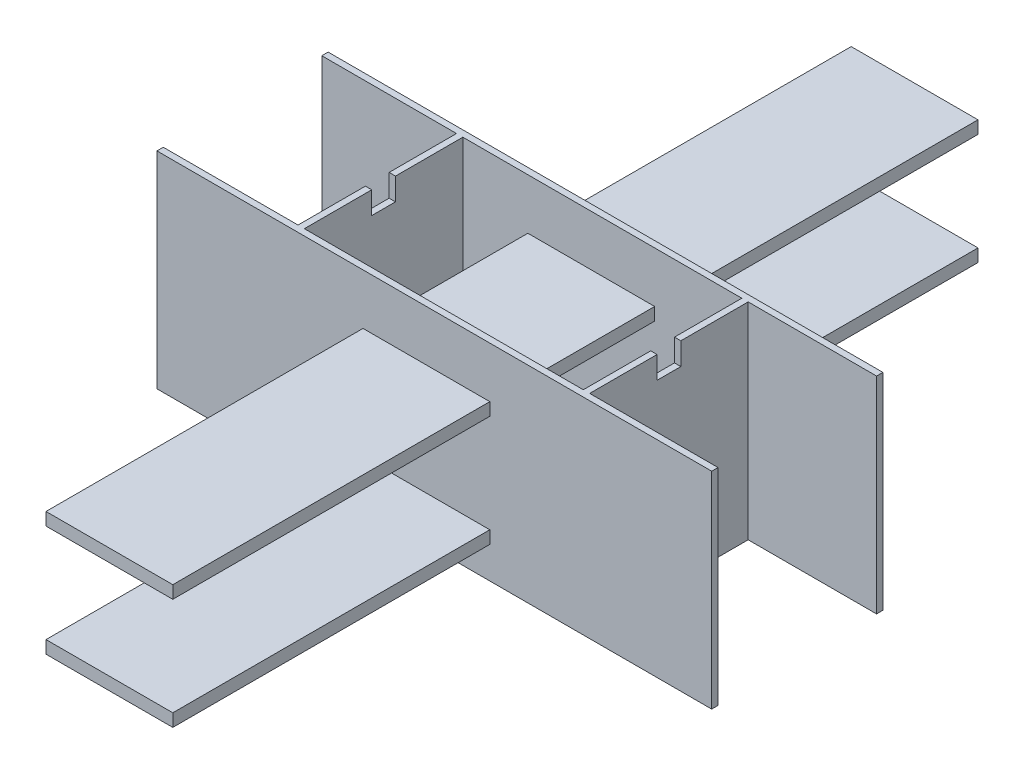
SolidWorks part; units mm, degrees
ref_plane "Front Plane" through (0, 0, 0) normal (0, 0, 1) x (1, 0, 0)
ref_plane "Top Plane" through (0, 0, 0) normal (0, 1, 0) x (1, 0, 0)
ref_plane "Right Plane" through (0, 0, 0) normal (1, 0, 0) x (0, 0, -1)
ref_plane "Plane1" through (0, 0, 25) normal (0, 0, 1) x (1, 0, 0)
sketch "Sketch1" plane through (0, 0, 25) normal (0, 0, 1) x (1, 0, 0)
  line L0 (0, 0) -> (21.8924, 0) construction
  line L1 (-87.5, 32.5) -> (87.5, 32.5)
  line L2 (-87.5, 32.5) -> (-87.5, -32.5)
  line L3 (-87.5, -32.5) -> (87.5, -32.5)
  line L4 (87.5, 32.5) -> (87.5, -32.5)
  line L5 (0, 0) -> (0, 16.4757) construction
  point P5 (0, 0)
  point P9 (0, 0)
  point P10 (-59.809, -32.5)
  dimension "D1" = 65
  dimension "D2" = 175
extrude "Boss-Extrude1" add sketch "Sketch1" along normal blind 2 contours L2 L3 L4 L1
ref_plane "Plane2" through (0, 0, -25) normal (0, 0, 1) x (1, 0, 0)
sketch "Sketch2" plane through (0, 0, -25) normal (0, 0, 1) x (1, 0, 0)
  line L0 (-87.5, -32.5) -> (87.5, -32.5) construction
  line L1 (-87.5, 32.5) -> (-87.5, -32.5) construction
  line L2 (-87.5, 32.5) -> (87.5, 32.5) construction
  line L3 (87.5, 32.5) -> (87.5, -32.5) construction
  line L4 (-87.5, -32.5) -> (87.5, -32.5)
  line L5 (-87.5, 32.5) -> (-87.5, -32.5)
  line L6 (-87.5, 32.5) -> (87.5, 32.5)
  line L7 (87.5, 32.5) -> (87.5, -32.5)
extrude "Boss-Extrude2" add sketch "Sketch2" against normal blind 2 separate body
sketch "Sketch3" plane through (0, 0, 0) normal (0, 0, 1) x (1, 0, 0)
  line L0 (87.5, 0) -> (17.5, 0) construction
  line L1 (87.5, -32.5) -> (87.5, 32.5) construction
  line L2 (17.5, 0) -> (17.5, 16.5) construction
  line L3 (17.5, 0) -> (17.5, -22.5) construction
  line L4 (87.5, 32.5) -> (-87.5, 32.5) construction
  line L5 (-87.5, -32.5) -> (87.5, -32.5) construction
  line L7 (17.5, 16.5) -> (-22.5, 16.5)
  line L8 (17.5, 16.5) -> (17.5, 12.5)
  line L9 (17.5, 12.5) -> (-22.5, 12.5)
  line L10 (-22.5, 16.5) -> (-22.5, 12.5)
  line L11 (17.5, -22.5) -> (-22.5, -22.5)
  line L12 (17.5, -22.5) -> (17.5, -18.5)
  line L13 (17.5, -18.5) -> (-22.5, -18.5)
  line L14 (-22.5, -22.5) -> (-22.5, -18.5)
  dimension "D1" = 70
  dimension "D2" = 16
  dimension "D3" = 10
  dimension "D4" = 4
  dimension "D5" = 4
  dimension "D6" = 40
  dimension "D7" = 40
extrude "Boss-Extrude3" add sketch "Sketch3" along normal blind 127 and the other way blind 127 contours L11 L14 L13 L12 | L7 L10 L9 L8
ref_plane "Plane3" through (45, 0, 0) normal (1, 0, 0) x (0, 0, -1)
ref_plane "Plane4" through (-45, 0, 0) normal (1, 0, 0) x (0, 0, -1)
sketch "Sketch4" plane through (45, 0, 0) normal (1, 0, 0) x (0, 0, -1)
  line L0 (3.749, 32.5) -> (25, 32.5)
  line L1 (-25, 32.5) -> (-3.749, 32.5)
  line L2 (-25, 32.5) -> (-25, -32.5)
  line L3 (-25, -32.5) -> (25, -32.5)
  line L4 (25, 32.5) -> (25, -32.5)
  line L6 (-3.749, 32.5) -> (-3.749, 25.458)
  line L7 (-3.749, 25.458) -> (3.749, 25.458)
  line L8 (3.749, 32.5) -> (3.749, 25.458)
  point P10 (3.749, 25.458)
extrude "Boss-Extrude4" add sketch "Sketch4" along normal blind 2
sketch "Sketch5" plane through (-45, 0, 0) normal (1, 0, 0) x (0, 0, -1)
  line L0 (-25, 32.5) -> (-25, -32.5) construction
  line L1 (-25, -32.5) -> (25, -32.5) construction
  line L2 (25, -32.5) -> (25, 32.5) construction
  line L3 (25, 32.5) -> (3.749, 32.5) construction
  line L4 (3.749, 32.5) -> (3.749, 25.458) construction
  line L5 (3.749, 25.458) -> (-3.749, 25.458) construction
  line L6 (-3.749, 25.458) -> (-3.749, 32.5) construction
  line L7 (-3.749, 32.5) -> (-25, 32.5) construction
  line L8 (-25, 32.5) -> (-25, -32.5)
  line L9 (-25, -32.5) -> (25, -32.5)
  line L10 (25, -32.5) -> (25, 32.5)
  line L11 (25, 32.5) -> (3.749, 32.5)
  line L12 (3.749, 32.5) -> (3.749, 25.458)
  line L13 (3.749, 25.458) -> (-3.749, 25.458)
  line L14 (-3.749, 25.458) -> (-3.749, 32.5)
  line L15 (-3.749, 32.5) -> (-25, 32.5)
extrude "Boss-Extrude5" add sketch "Sketch5" along normal blind 2
